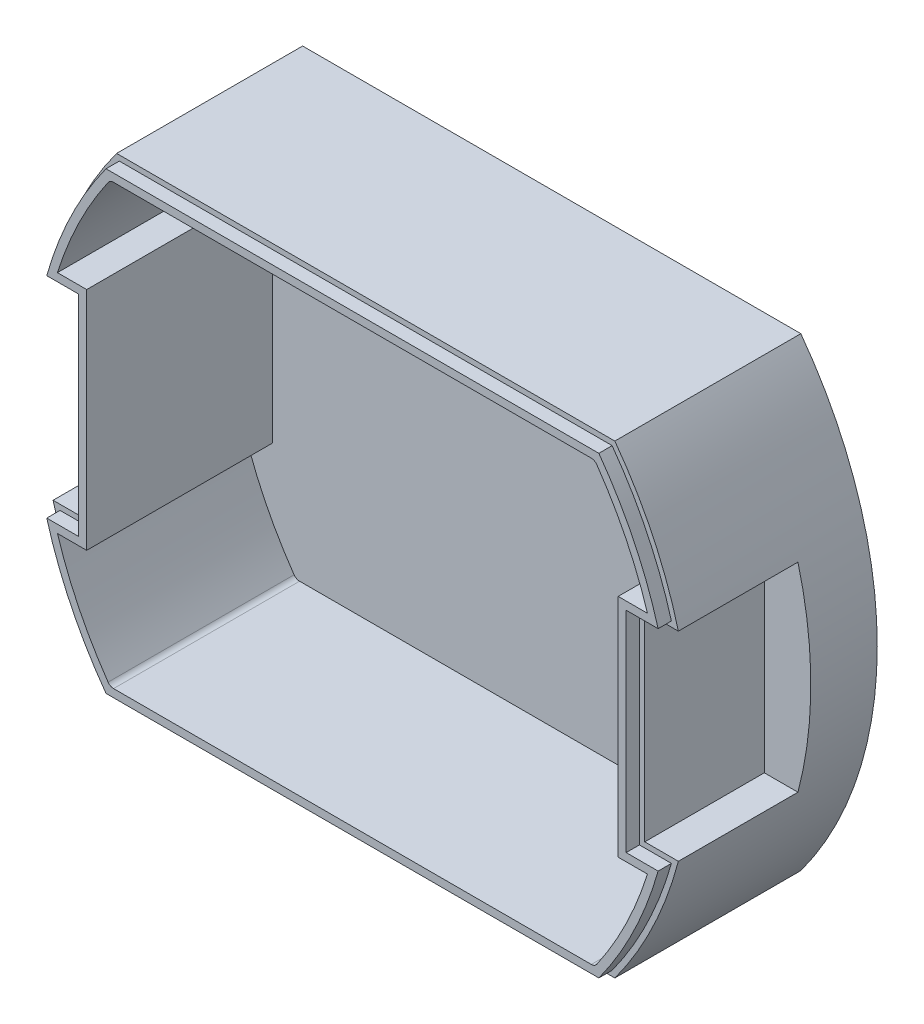
SolidWorks part; units mm, degrees
ref_plane "Front Plane" through (0, 0, 0) normal (0, 0, 1) x (1, 0, 0)
ref_plane "Top Plane" through (0, 0, 0) normal (0, 1, 0) x (1, 0, 0)
ref_plane "Right Plane" through (0, 0, 0) normal (1, 0, 0) x (0, 0, -1)
sketch "Sketch1" plane through (0, 0, 0) normal (0, 0, 1) x (1, 0, 0)
  line L0 (37.5, 70) -> (37.5, 0) construction
  line L1 (0, 0) -> (75, 0)
  line L3 (0, 70) -> (75, 70)
  line L5 (-11.5021, 35) -> (86.5021, 35) construction
  arc A0 (0, 70) -> (0, 0) centre (47.5, 35) ccw
  arc A1 (75, 70) -> (75, 0) centre (27.5, 35) cw
  dimension "D1" = 75
  dimension "D2" = 70
extrude "Boss-Extrude4" add sketch "Sketch1" along normal blind 10
sketch "Sketch4" plane through (0, 0, 10) normal (0, 0, 1) x (1, 0, 0)
  line L0 (37.5, 70) -> (37.5, 0) construction
  line L1 (75, 70) -> (0, 70) construction
  line L2 (0, 0) -> (75, 0) construction
  line L3 (-11.5021, 35) -> (86.5021, 35) construction
  line L4 (-11.5021, 20) -> (86.5021, 20) construction
  line L5 (-11.5021, 50) -> (86.5021, 50) construction
  line L6 (-11.5021, 35) -> (-4.5021, 35) construction
  line L11 (79.5021, 20) -> (84.5636, 20)
  line L14 (79.5021, 50) -> (84.5636, 50)
  line L15 (0, 0) -> (75, 0)
  line L16 (75, 70) -> (0, 70)
  line L17 (79.5021, 50) -> (79.5021, 20)
  line L18 (75, 70) -> (75, 0) construction
  line L19 (0, 70) -> (0, 0) construction
  line L20 (-4.5021, 50) -> (-9.5636, 50)
  line L21 (-4.5021, 20) -> (-9.5636, 20)
  line L22 (-4.5021, 50) -> (-4.5021, 20)
  arc A0 (0, 70) -> (0, 0) centre (47.5, 35) ccw construction
  arc A1 (75, 0) -> (75, 70) centre (27.5, 35) ccw construction
  arc A4 (84.5636, 20) -> (75, 0) centre (27.5, 35) cw
  arc A5 (75, 70) -> (84.5636, 50) centre (27.5, 35) cw
  arc A7 (-9.5636, 20) -> (0, 0) centre (47.5, 35) ccw
  arc A8 (0, 70) -> (-9.5636, 50) centre (47.5, 35) ccw
  point P21 (82.0328, 50)
  point P27 (47.5, 35)
  point P28 (-7.0328, 50)
  dimension "D1" = 15
  dimension "D3" = 7
  dimension "D4" = 75
  dimension "D2" = 15
extrude "Boss-Extrude10" add sketch "Sketch4" along normal blind 18
sketch "Sketch9" plane through (0, 0, 28) normal (0, 0, 1) x (1, 0, 0)
  line L24 (-8.5165, 50.8) -> (-3.7021, 50.8)
  line L25 (-3.7021, 50.8) -> (-3.7021, 19.2)
  line L26 (-3.7021, 19.2) -> (-8.5165, 19.2)
  line L27 (0.406, 0.8) -> (74.594, 0.8)
  line L28 (83.5165, 19.2) -> (78.7021, 19.2)
  line L29 (78.7021, 19.2) -> (78.7021, 50.8)
  line L30 (78.7021, 50.8) -> (83.5165, 50.8)
  line L31 (74.594, 69.2) -> (0.406, 69.2)
  line L32 (-8.5165, 50.8) -> (-3.7021, 50.8)
  line L33 (-3.7021, 50.8) -> (-3.7021, 19.2)
  line L34 (-3.7021, 19.2) -> (-8.5165, 19.2)
  line L35 (0.406, 0.8) -> (74.594, 0.8)
  line L36 (83.5165, 19.2) -> (78.7021, 19.2)
  line L37 (78.7021, 19.2) -> (78.7021, 50.8)
  line L38 (78.7021, 50.8) -> (83.5165, 50.8)
  line L39 (74.594, 69.2) -> (0.406, 69.2)
  arc A12 (0.406, 69.2) -> (-8.5165, 50.8) centre (47.5, 35) ccw
  arc A13 (-8.5165, 19.2) -> (0.406, 0.8) centre (47.5, 35) ccw
  arc A14 (74.594, 0.8) -> (83.5165, 19.2) centre (27.5, 35) ccw
  arc A15 (83.5165, 50.8) -> (74.594, 69.2) centre (27.5, 35) ccw
  arc A16 (0.406, 69.2) -> (-8.5165, 50.8) centre (47.5, 35) ccw
  arc A17 (-8.5165, 19.2) -> (0.406, 0.8) centre (47.5, 35) ccw
  arc A18 (74.594, 0.8) -> (83.5165, 19.2) centre (27.5, 35) ccw
  arc A19 (83.5165, 50.8) -> (74.594, 69.2) centre (27.5, 35) ccw
  dimension "D1" = 0.8
extrude "Boss-Extrude11" add sketch "Sketch9" along normal blind 2
sketch "Sketch10" plane through (0, 0, 30) normal (0, 0, 1) x (1, 0, 0)
  line L0 (-8.5165, 50.8) -> (83.5165, 50.8) construction
  line L1 (-8.5165, 19.2) -> (83.5165, 19.2) construction
  line L2 (-8.5165, 53.8) -> (83.5165, 53.8) construction
  line L3 (-8.5165, 16.2) -> (83.5165, 16.2) construction
  line L4 (37.5, 69.2) -> (37.5, 0.8) construction
  line L5 (74.594, 69.2) -> (0.406, 69.2) construction
  line L6 (0.406, 0.8) -> (74.594, 0.8) construction
  line L7 (-6.9081, 52) -> (-2.5021, 52)
  line L8 (78.7021, 50.8) -> (78.7021, 8.2566) construction
  line L9 (1.5409, 68) -> (73.4591, 68)
  line L10 (37.5, 35) -> (102.2068, 35) construction
  line L11 (37.5, 35) -> (-45.1921, 35) construction
  line L13 (0, 70) -> (0, 0) construction
  line L14 (75, 70) -> (75, 0) construction
  line L16 (-3.7021, 50.8) -> (-3.7021, 8.2566) construction
  line L17 (-2.5021, 52) -> (-2.5021, 18)
  line L18 (81.9081, 52) -> (77.5021, 52)
  line L25 (77.5021, 52) -> (77.5021, 18)
  line L26 (81.9081, 18) -> (77.5021, 18)
  line L27 (1.5409, 2) -> (73.4591, 2)
  line L28 (-6.9081, 18) -> (-2.5021, 18)
  arc A10 (1.377, 68.4949) -> (-7.3615, 50.4742) centre (47.5, 35) ccw
  arc A11 (0.7203, 67.5714) -> (-6.9081, 52) centre (47.5, 35) ccw
  arc A12 (0.7203, 67.5714) -> (1.5409, 68) centre (1.5409, 67) cw
  arc A33 (74.2797, 67.5714) -> (73.4591, 68) centre (73.4591, 67) ccw
  arc A34 (74.2797, 67.5714) -> (81.9081, 52) centre (27.5, 35) cw
  arc A35 (74.2797, 2.4286) -> (81.9081, 18) centre (27.5, 35) ccw
  arc A36 (74.2797, 2.4286) -> (73.4591, 2) centre (73.4591, 3) cw
  arc A37 (0.7203, 2.4286) -> (1.5409, 2) centre (1.5409, 3) ccw
  arc A38 (0.7203, 2.4286) -> (-6.9081, 18) centre (47.5, 35) cw
  point P19 (0, 0)
  point P20 (0, 0)
  point P32 (-2.5021, 35)
  point P35 (37.5, 68)
  point P40 (77.5021, 35)
  point P64 (-2.5021, 35)
  point P71 (37.5, 2)
  dimension "D3" = 1.2
  dimension "D7" = 1
  dimension "D1" = 3
  dimension "D2" = 3
  dimension "D4" = 1.2
extrude "Cut-Extrude8" cut sketch "Sketch10" against normal blind 28
sketch "Sketch13" plane through (0, 0, 10) normal (0, 0, 1) x (1, 0, 0)
  line L0 (86.5021, 35) -> (-11.5021, 35) construction
  line L1 (37.5, 70) -> (37.5, 0) construction
  line L2 (75, 70) -> (0, 70) construction
  line L3 (0, 0) -> (75, 0) construction
  line L4 (86.1963, 41) -> (-11.5021, 41) construction
  line L5 (86.1963, 29) -> (-11.5021, 29) construction
  line L6 (86.5021, 41) -> (-11.5021, 41) construction
  line L7 (86.5021, 29) -> (-11.5021, 29) construction
  arc A1 (84.5636, 20) -> (84.5636, 50) centre (27.5, 35) ccw construction
  arc A2 (-9.5636, 50) -> (-9.5636, 20) centre (47.5, 35) ccw construction
  point P20 (86.1963, 41)
  dimension "D1" = 6
  dimension "D2" = 6
